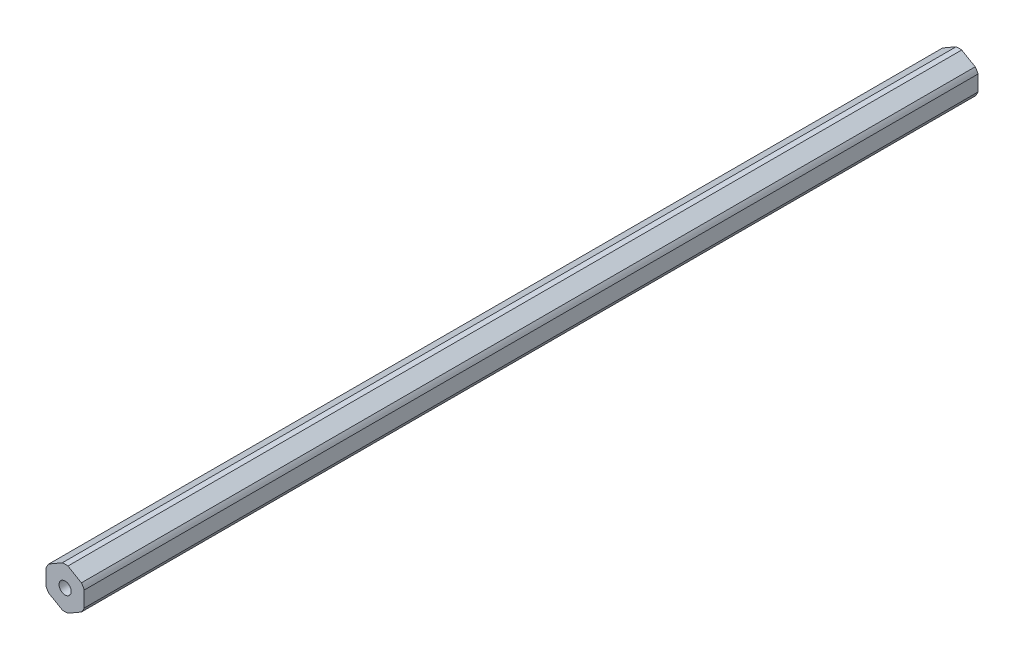
SolidWorks part; units mm, degrees
ref_plane "Front Plane" through (0, 0, 0) normal (0, 0, 1) x (1, 0, 0)
ref_plane "Top Plane" through (0, 0, 0) normal (0, 1, 0) x (1, 0, 0)
ref_plane "Right Plane" through (0, 0, 0) normal (1, 0, 0) x (0, 0, -1)
sketch "Sketch1" plane through (0, 0, 0) normal (0, 0, 1) x (1, 0, 0)
  line L1 (0, 7.3323) -> (-6.35, 3.6662)
  line L2 (-6.35, 3.6662) -> (-6.35, -3.6662)
  line L3 (-6.35, -3.6662) -> (0, -7.3323)
  line L4 (0, -7.3323) -> (6.35, -3.6662)
  line L5 (6.35, -3.6662) -> (6.35, 3.6662)
  line L6 (6.35, 3.6662) -> (0, 7.3323)
  circle A0 centre (0, 0) radius 6.35 construction
  circle A1 centre (0, 0) radius 6.858
  dimension "D1" = 12.7
  dimension "D2" = 13.716
extrude "Boss-Extrude1" add sketch "Sketch1" along normal mid plane 297.053 contours L5 A1 L6 L1 L2 L3 L4
sketch "Sketch2" plane through (0, 0, 148.5265) normal (0, 0, 1) x (1, 0, 0)
  circle A0 centre (0, 0) radius 2.0193
  dimension "D1" = 4.0386
extrude "Cut-Extrude1" cut sketch "Sketch2" against normal through all
